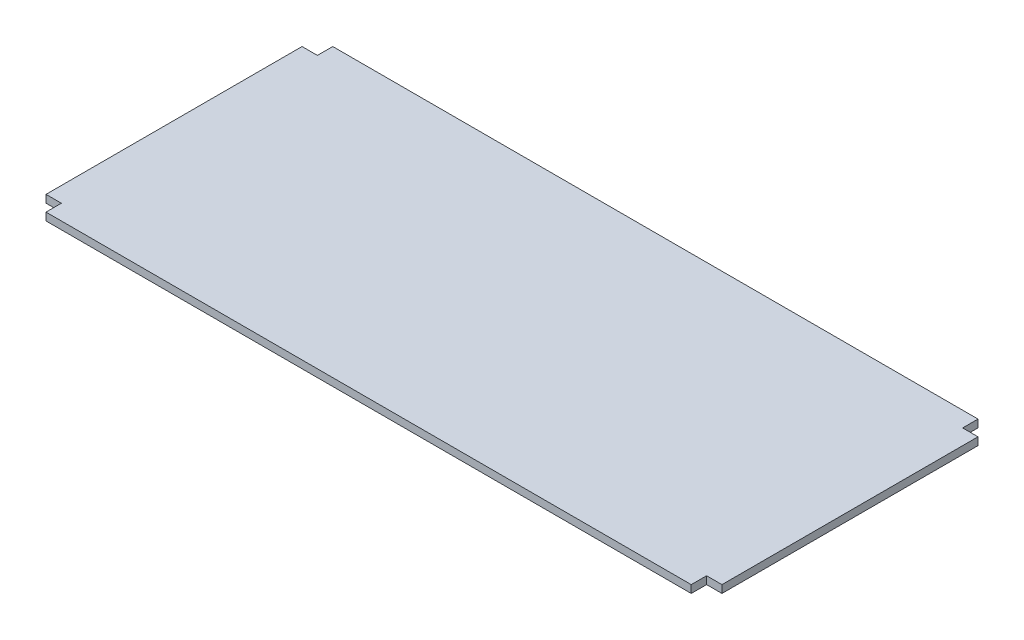
SolidWorks part; units mm, degrees
material "Pine"
ref_plane "Front Plane" through (0, 0, 0) normal (0, 0, 1) x (1, 0, 0)
ref_plane "Top Plane" through (0, 0, 0) normal (0, 1, 0) x (1, 0, 0)
ref_plane "Right Plane" through (0, 0, 0) normal (1, 0, 0) x (0, 0, -1)
sketch "Sketch1" plane through (0, 0, 0) normal (0, 1, 0) x (1, 0, 0)
  line L1 (800.1, -355.6) -> (-800.1, -355.6)
  line L2 (838.2, -317.5) -> (838.2, 317.5)
  line L3 (800.1, 355.6) -> (-800.1, 355.6)
  line L4 (-838.2, -317.5) -> (-838.2, 317.5)
  line L5 (838.2, -355.6) -> (-838.2, 355.6) construction
  line L6 (838.2, 355.6) -> (-838.2, -355.6) construction
  line L9 (-838.2, -317.5) -> (-800.1, -317.5)
  line L10 (-800.1, -355.6) -> (-800.1, -317.5)
  line L13 (-838.2, 317.5) -> (-800.1, 317.5)
  line L14 (-800.1, 355.6) -> (-800.1, 317.5)
  line L17 (838.2, 317.5) -> (800.1, 317.5)
  line L18 (800.1, 355.6) -> (800.1, 317.5)
  line L21 (838.2, -317.5) -> (800.1, -317.5)
  line L22 (800.1, -355.6) -> (800.1, -317.5)
  point P0 (0, 0)
  dimension "D1" = 711.2
  dimension "D2" = 1676.4
  dimension "D3" = 38.1
  dimension "D4" = 38.1
  dimension "D5" = 38.1
  dimension "D6" = 38.1
extrude "Boss-Extrude1" add sketch "Sketch1" along normal blind 19.05
